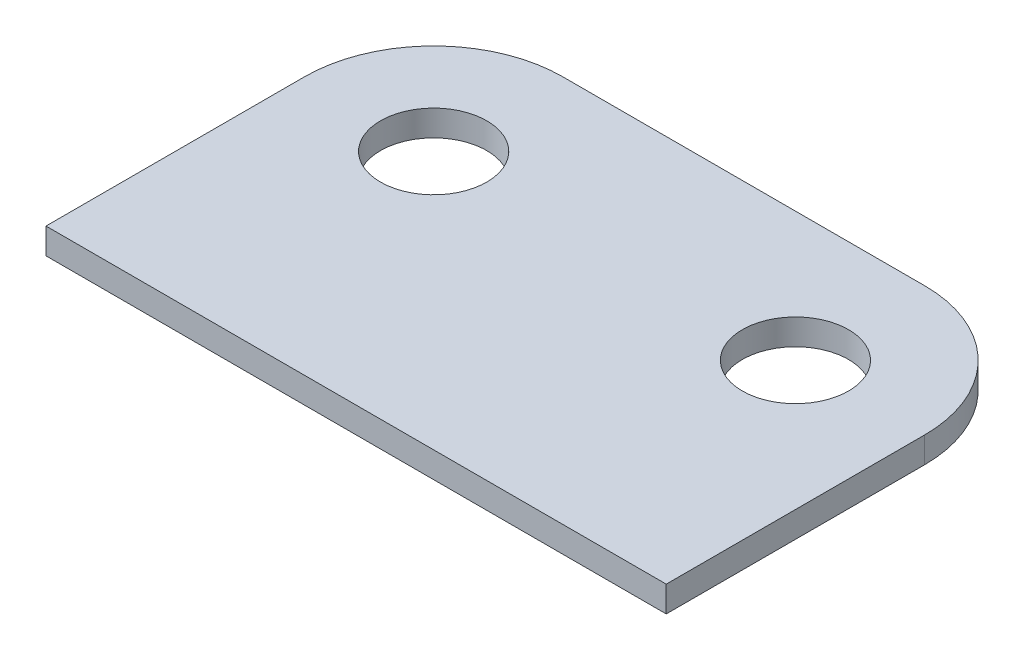
SolidWorks part; units mm, degrees
material "AISI 1020"
ref_plane "Front Plane" through (0, 0, 0) normal (0, 0, 1) x (1, 0, 0)
ref_plane "Top Plane" through (0, 0, 0) normal (0, 1, 0) x (1, 0, 0)
ref_plane "Right Plane" through (0, 0, 0) normal (1, 0, 0) x (0, 0, -1)
sketch "Sketch1" plane through (0, 0, 0) normal (0, 1, 0) x (1, 0, 0)
  line L0 (-19.05, 0) -> (19.05, 0)
  line L1 (19.05, 0) -> (19.05, 15.875)
  line L2 (-19.05, 15.875) -> (-19.05, 0)
  line L3 (-11.1125, 23.8125) -> (11.1125, 23.8125)
  arc A0 (19.05, 15.875) -> (11.1125, 23.8125) centre (11.1125, 15.875) ccw
  arc A2 (-11.1125, 23.8125) -> (-19.05, 15.875) centre (-11.1125, 15.875) ccw
  circle A3 centre (-11.1125, 15.875) radius 3.2639
  circle A4 centre (11.1125, 15.875) radius 3.2639
  point P4 (0, 0)
  dimension "D1" = 6.5278
  dimension "D2" = 38.1
  dimension "D4" = 22.225
  dimension "D3" = 15.875
extrude "Boss-Extrude1" add sketch "Sketch1" along normal blind 1.5875
